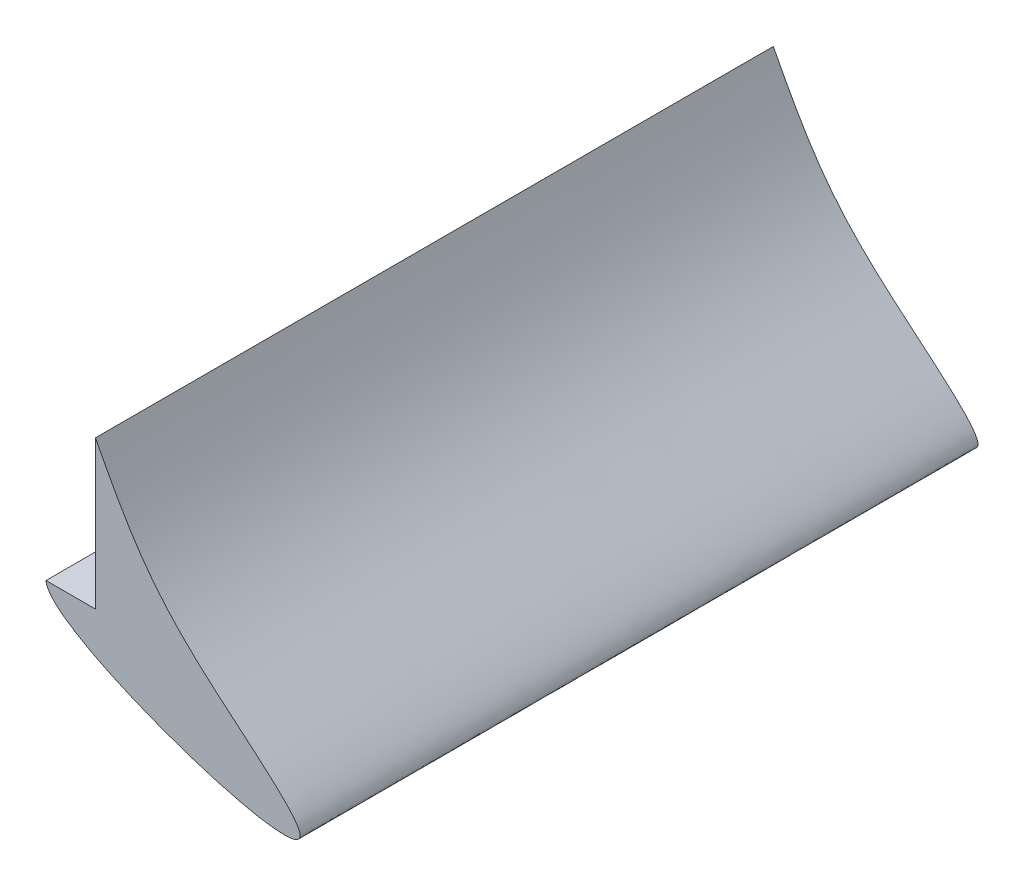
SolidWorks part; units mm, degrees
ref_plane "Front Plane" through (0, 0, 0) normal (0, 0, 1) x (1, 0, 0)
ref_plane "Top Plane" through (0, 0, 0) normal (0, 1, 0) x (1, 0, 0)
ref_plane "Right Plane" through (0, 0, 0) normal (1, 0, 0) x (0, 0, -1)
sketch "Sketch1" plane through (0, 0, 0) normal (0, 0, 1) x (1, 0, 0)
  line L0 (0, 0) -> (5, 0)
  line L1 (5, 0) -> (5, 15)
  spline S0 degree 3 poles (0, 0) (0.2875, -4.1896) (37.8177, -16.8739) (11.9308, 2.2766) (8.321, 8.6462) (5, 15) knots 0 0 0 0 0.463325 0.690507 1 1 1 1
extrude "Boss-Extrude2" add sketch "Sketch1" along normal blind 68.58
